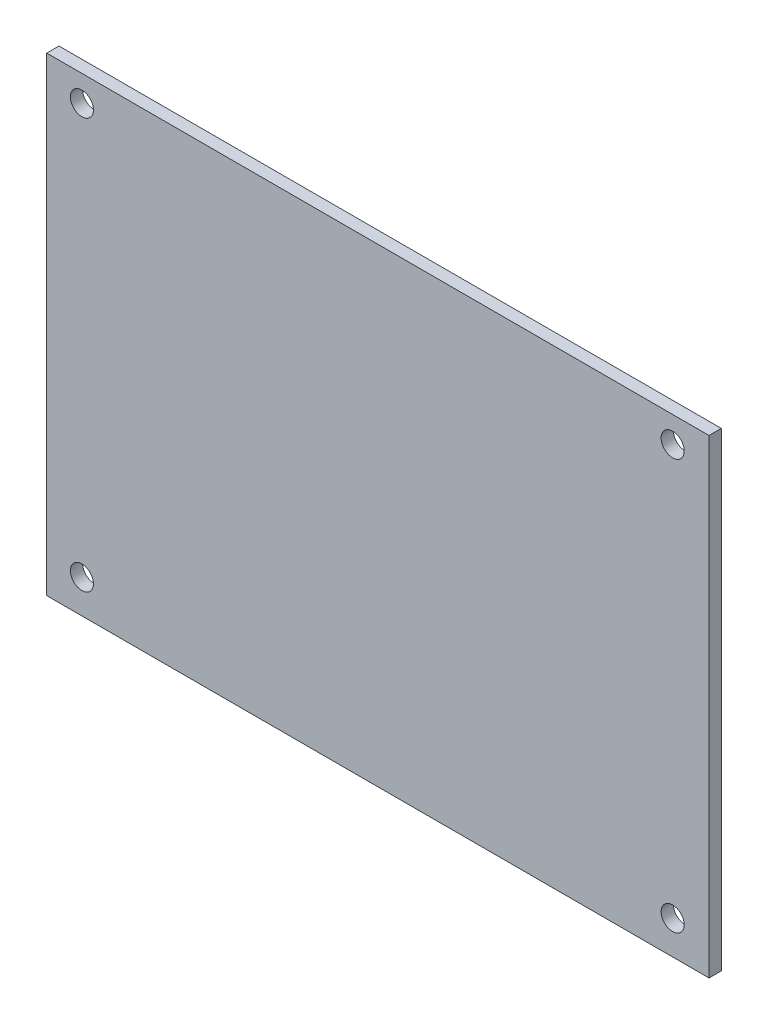
SolidWorks part; units mm, degrees
material "Płyta przetworzona, prosta"
ref_plane "Płaszczyzna przednia" through (0, 0, 0) normal (0, 0, 1) x (1, 0, 0)
ref_plane "Płaszczyzna górna" through (0, 0, 0) normal (0, 1, 0) x (1, 0, 0)
ref_plane "Płaszczyzna prawa" through (0, 0, 0) normal (1, 0, 0) x (0, 0, -1)
sketch "Szkic1" plane through (0, 0, 0) normal (0, 0, 1) x (1, 0, 0)
  line L1 (-45.88, 32.55) -> (45.88, 32.55)
  line L2 (-45.88, 32.55) -> (-45.88, -32.55)
  line L3 (-45.88, -32.55) -> (45.88, -32.55)
  line L4 (45.88, 32.55) -> (45.88, -32.55)
  line L5 (-45.88, 32.55) -> (45.88, -32.55) construction
  line L6 (-45.88, -32.55) -> (45.88, 32.55) construction
  point P0 (0, 0)
  dimension "D1" = 91.76
  dimension "D2" = 65.1
extrude "Dodanie-wyciągnięcie1" add sketch "Szkic1" along normal blind 1.7
sketch "Szkic2" plane through (0, 0, 1.7) normal (0, 0, 1) x (1, 0, 0)
  line L0 (-39.4249, 27.3757) -> (39.4249, 27.3757) construction
  line L1 (-39.4249, 27.3757) -> (-39.4249, -27.3757) construction
  line L2 (-39.4249, -27.3757) -> (39.4249, -27.3757) construction
  line L3 (39.4249, 27.3757) -> (39.4249, -27.3757) construction
  line L4 (-39.4249, 27.3757) -> (39.4249, -27.3757) construction
  line L5 (-39.4249, -27.3757) -> (39.4249, 27.3757) construction
  point P0 (0, 0)
  dimension "D1" = 54.7514
  dimension "D2" = 78.8497
hole_wizard "Otwór Ø3.2 (3.2)1" positions "Szkic3" profile "Szkic4" hole size "Ø3.2" standard "Ansi Metric"
sketch "Szkic3" plane through (0, 0, 1.7) normal (0, 0, 1) x (1, 0, 0)
  line L0 (45.88, 32.55) -> (-45.88, 32.55) construction
  line L1 (-45.88, 32.55) -> (-45.88, -32.55) construction
  point P0 (-41.005, 28.945)
  point P2 (40.845, 28.945)
  point P4 (40.845, -27.905)
  point P6 (-41.005, -27.905)
  dimension "D1" = 56.85
  dimension "D2" = 81.85
  dimension "D3" = 3.605
  dimension "D4" = 4.875
sketch "Szkic4" plane through (-41.005, 28.945, 1.7) normal (1, 0, 0) x (0, -1, 0)
  line L0 (0, 0) -> (0, 6.9614)
  line L1 (0, 6.9614) -> (1.6, 6)
  line L2 (1.6, 6) -> (1.6, 0)
  line L5 (1.6, 0) -> (0, 0)
  line L10 (0, 6.9614) -> (-1.6, 6) construction
  line L11 (0, -6.35) -> (0, 107.95) construction
  dimension "Średnica otworu" = 3.2
  dimension "Głębokość otworu" = 6
  dimension "Kąt wiertła" = 118
